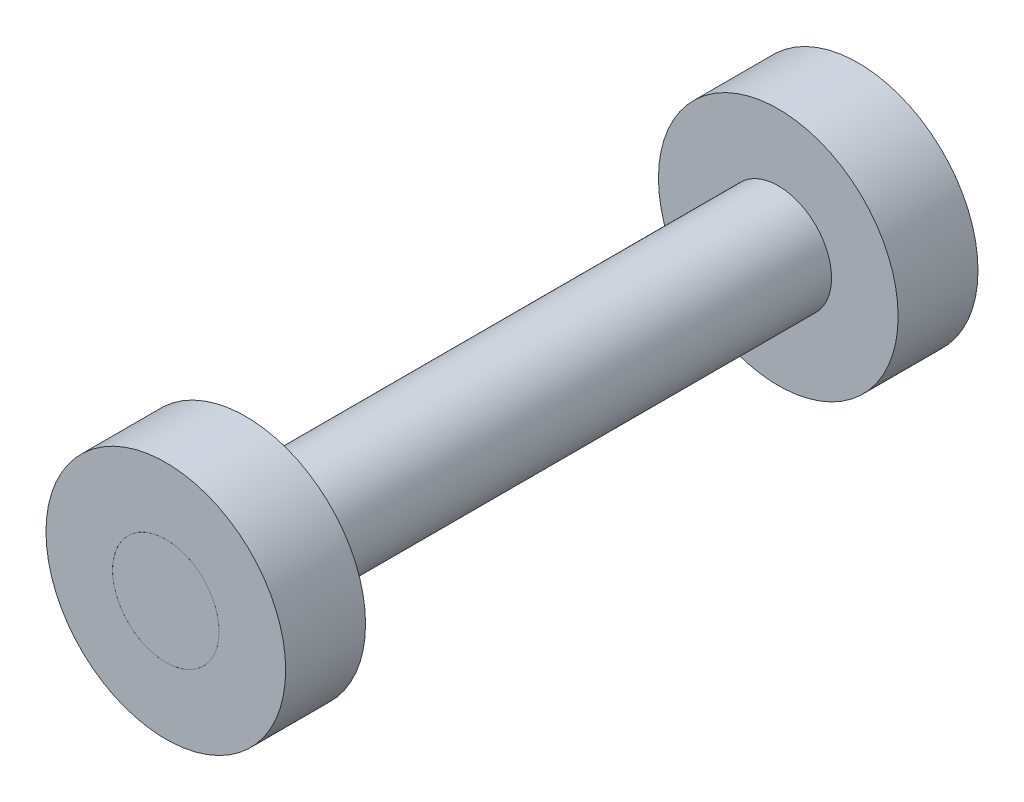
SolidWorks part; units mm, degrees
ref_plane "Alzado" through (0, 0, 0) normal (0, 0, 1) x (1, 0, 0)
ref_plane "Planta" through (0, 0, 0) normal (0, 1, 0) x (1, 0, 0)
ref_plane "Vista lateral" through (0, 0, 0) normal (1, 0, 0) x (0, 0, -1)
sketch "Croquis1" plane through (0, 0, 0) normal (0, 0, 1) x (1, 0, 0)
  circle A0 centre (0, 0) radius 4.5
  dimension "D1" = 9
extrude "Saliente-Extruir1" add sketch "Croquis1" along normal blind 3
sketch "Croquis2" plane through (0, 0, 0) normal (0, 0, 1) x (1, 0, 0)
  circle A0 centre (0, 0) radius 2
  dimension "D1" = 4
extrude "Saliente-Extruir2" add sketch "Croquis2" along normal blind 26
sketch "Croquis4" plane through (0, 0, 0) normal (0, 0, 1) x (1, 0, 0)
  circle A0 centre (0, 0) radius 4.5
  circle A1 centre (0, 0) radius 2
  circle A2 centre (0, 0) radius 2 construction
  dimension "D1" = 9
extrude "Saliente-Extruir3" add sketch "Croquis4" along normal blind 3 from offset 23 separate body
